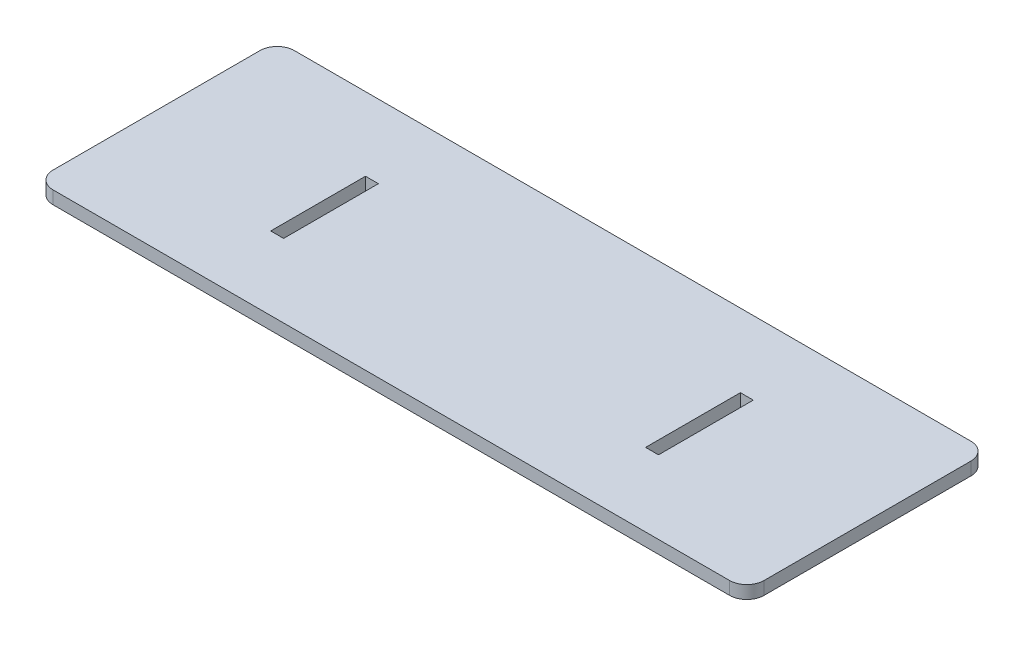
SolidWorks part; units mm, degrees
ref_plane "Front Plane" through (0, 0, 0) normal (0, 0, 1) x (1, 0, 0)
ref_plane "Top Plane" through (0, 0, 0) normal (0, 1, 0) x (1, 0, 0)
ref_plane "Right Plane" through (0, 0, 0) normal (1, 0, 0) x (0, 0, -1)
sketch "Sketch1" plane through (0, 0, 0) normal (0, 1, 0) x (1, 0, 0)
  line L0 (-78.5, -28) -> (78.5, -28)
  line L1 (82.5, -24) -> (82.5, 24)
  line L2 (78.5, 28) -> (-78.5, 28)
  line L3 (-82.5, 24) -> (-82.5, -24)
  arc A0 (78.5, -28) -> (82.5, -24) centre (78.5, -24) ccw
  arc A1 (82.5, 24) -> (78.5, 28) centre (78.5, 24) ccw
  arc A2 (-78.5, 28) -> (-82.5, 24) centre (-78.5, 24) ccw
  arc A3 (-82.5, -24) -> (-78.5, -28) centre (-78.5, -24) ccw
extrude "Boss-Extrude1" add sketch "Sketch1" along normal blind 3
sketch "Sketch2" plane through (0, 0, 0) normal (0, 1, 0) x (1, 0, 0)
  line L0 (-45, 11) -> (-42, 11)
  line L1 (-42, 11) -> (-42, -11)
  line L2 (-42, -11) -> (-45, -11)
  line L3 (-45, -11) -> (-45, 11)
  line L4 (42, 11) -> (45, 11)
  line L5 (45, 11) -> (45, -11)
  line L6 (45, -11) -> (42, -11)
  line L7 (42, -11) -> (42, 11)
extrude "Cut-Extrude1" cut sketch "Sketch2" against normal through all and the other way through all
